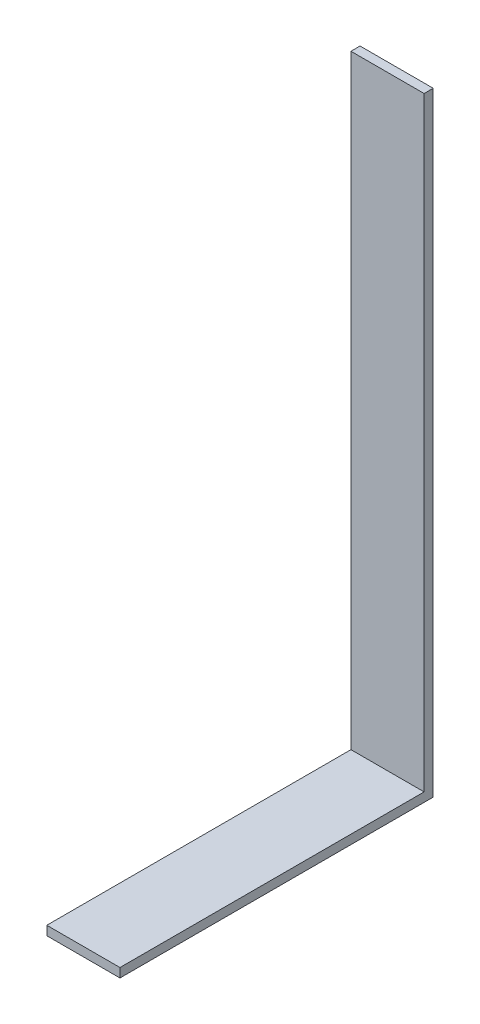
SolidWorks part; units mm, degrees
ref_plane "Alzado" through (0, 0, 0) normal (0, 0, 1) x (1, 0, 0)
ref_plane "Planta" through (0, 0, 0) normal (0, 1, 0) x (1, 0, 0)
ref_plane "Vista lateral" through (0, 0, 0) normal (1, 0, 0) x (0, 0, -1)
sketch "Croquis1" plane through (0, 0, 0) normal (0, 0, 1) x (1, 0, 0)
  line L1 (-25.4, 3.155) -> (25.4, 3.155)
  line L2 (-25.4, 3.155) -> (-25.4, -3.155)
  line L3 (-25.4, -3.155) -> (25.4, -3.155)
  line L4 (25.4, 3.155) -> (25.4, -3.155)
  line L5 (-25.4, 3.155) -> (25.4, -3.155) construction
  line L6 (-25.4, -3.155) -> (25.4, 3.155) construction
  point P0 (0, 0)
  dimension "D1" = 50.8
  dimension "D2" = 6.31
extrude "Saliente-Extruir1" add sketch "Croquis1" along normal blind 285.44
sketch "Croquis3" plane through (0, -3.155, 0) normal (0, -1, 0) x (1, 0, 0)
  line L0 (-25.4, 285.44) -> (-25.4, 0) construction
  line L1 (25.4, 0) -> (-25.4, 0)
  line L2 (25.4, 0) -> (25.4, 6.31)
  line L3 (25.4, 6.31) -> (-25.4, 6.31)
  line L4 (-25.4, 0) -> (-25.4, 6.31)
  line L5 (25.4, 0) -> (-25.4, 6.31) construction
  line L6 (25.4, 6.31) -> (-25.4, 0) construction
  line L7 (25.4, 285.44) -> (25.4, 0) construction
  line L8 (-25.4, 0) -> (25.4, 0) construction
  point P0 (0, 3.155)
  dimension "D1" = 6.31
extrude "Saliente-Extruir2" add sketch "Croquis3" against normal blind 544.51
sketch "Croquis4" plane through (0, 541.355, 0) normal (0, 1, 0) x (1, 0, 0)
  line L0 (25.4, -6.31) -> (-25.4, -6.31)
  line L1 (-25.4, -6.31) -> (-25.4, 0)
  line L2 (-25.4, 0) -> (25.4, 0)
  line L3 (25.4, 0) -> (25.4, -6.31)
  line L4 (0, 0) -> (0, -6.31) construction
  line L5 (0, -6.31) -> (0, -3.155) construction
  line L6 (0, -3.155) -> (-25.4, -3.155) construction
sketch3d "Croquis3D1"
  line L0 (0, 541.355, 3.155) -> (0, 551.355, 3.155)
  line L2 (0, 551.355, 3.155) -> (0, 551.355, 44.965)
  line L3 (0, 551.355, 44.965) -> (0, 634.515, 44.965)
  dimension "D1" = 10
  dimension "D2" = 41.81
  dimension "D3" = 83.16
sweep "Barrer1" add profiles "Croquis4" path "Croquis3D1"
sketch "Croquis5" plane through (0, -3.155, 0) normal (0, -1, 0) x (1, 0, 0)
  line L0 (-25.4, 285.44) -> (-25.4, 217.44)
  line L1 (-25.4, 285.44) -> (-25.4, 0) construction
  line L2 (-25.4, 217.44) -> (25.4, 217.44)
  line L3 (25.4, 285.44) -> (25.4, 0) construction
  line L4 (25.4, 217.44) -> (25.4, 285.44)
  line L5 (25.4, 285.44) -> (-25.4, 285.44)
  dimension "D1" = 68
extrude "Cortar-Extruir1" cut sketch "Croquis5" against normal blind 10
sketch "Croquis11" plane through (25.4, 0, 0) normal (1, 0, 0) x (0, 0, -1)
  line L0 (-48.12, 634.515) -> (-48.12, 423.015)
  line L1 (-48.12, 423.015) -> (0, 423.015)
  line L2 (0, -3.155) -> (0, 554.51) construction
  line L3 (0, 423.015) -> (0, 634.515)
  line L4 (0, 634.515) -> (-48.12, 634.515)
  dimension "D1" = 211.5
extrude "Cortar-Extruir2" cut sketch "Croquis11" against normal blind 50.8
